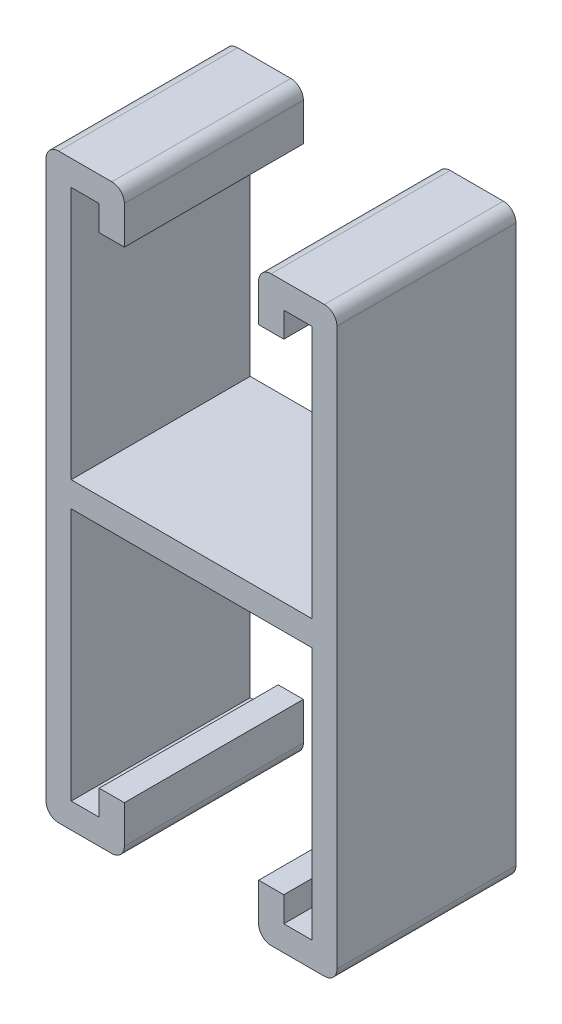
SolidWorks part; units mm, degrees
ref_plane "Plane1" through (0, 0, 0) normal (0, 0, 1) x (1, 0, 0)
ref_plane "Plane2" through (0, 0, 0) normal (0, 1, 0) x (1, 0, 0)
ref_plane "Plane3" through (0, 0, 0) normal (1, 0, 0) x (0, 0, -1)
sketch "Sketch1" plane through (0, 0, 0) normal (0, 0, 1) x (1, 0, 0)
  line L0 (-11.3109, 41.275) -> (-18.8516, 41.275)
  line L1 (-20.6375, 39.4891) -> (-20.6375, -39.4891)
  line L2 (25.727, 0) -> (-25.0678, 0) construction
  line L3 (20.6375, -39.4891) -> (20.6375, 39.4891)
  line L4 (18.8516, 41.275) -> (11.3109, 41.275)
  line L5 (9.525, 39.4891) -> (9.525, 34.1313)
  line L6 (-9.525, 39.4891) -> (-9.525, 34.1313)
  line L7 (-13.0969, 37.7031) -> (-13.0969, 34.1313)
  line L8 (-13.0969, 37.7031) -> (-17.0656, 37.7031)
  line L9 (-17.0656, 37.7031) -> (-17.0656, 1.7859)
  line L10 (-17.0656, 1.7859) -> (17.0656, 1.7859)
  line L11 (17.0656, 1.7859) -> (17.0656, 37.7031)
  line L12 (17.0656, 37.7031) -> (13.0969, 37.7031)
  line L13 (13.0969, 37.7031) -> (13.0969, 34.1313)
  line L14 (-13.0969, 34.1313) -> (-9.525, 34.1313)
  line L15 (9.525, 34.1313) -> (13.0969, 34.1313)
  line L16 (-11.3109, -41.275) -> (-18.8516, -41.275)
  line L17 (-13.0969, -37.7031) -> (-17.0656, -37.7031)
  line L18 (-13.0969, -37.7031) -> (-13.0969, -34.1313)
  line L19 (-9.525, -39.4891) -> (-9.525, -34.1313)
  line L20 (-13.0969, -34.1313) -> (-9.525, -34.1313)
  line L21 (18.8516, -41.275) -> (11.3109, -41.275)
  line L22 (9.525, -39.4891) -> (9.525, -34.1313)
  line L23 (9.525, -34.1313) -> (13.0969, -34.1313)
  line L24 (13.0969, -37.7031) -> (13.0969, -34.1313)
  line L25 (17.0656, -37.7031) -> (13.0969, -37.7031)
  line L26 (17.0656, -1.7859) -> (17.0656, -37.7031)
  line L27 (-17.0656, -37.7031) -> (-17.0656, -1.7859)
  line L28 (-17.0656, -1.7859) -> (17.0656, -1.7859)
  arc A0 (-11.3109, 41.275) -> (-9.525, 39.4891) centre (-11.3109, 39.4891) cw
  arc A1 (-20.6375, 39.4891) -> (-18.8516, 41.275) centre (-18.8516, 39.4891) cw
  arc A2 (-11.3109, -41.275) -> (-9.525, -39.4891) centre (-11.3109, -39.4891) ccw
  arc A3 (-20.6375, -39.4891) -> (-18.8516, -41.275) centre (-18.8516, -39.4891) ccw
  arc A4 (18.8516, 41.275) -> (20.6375, 39.4891) centre (18.8516, 39.4891) cw
  arc A5 (9.525, 39.4891) -> (11.3109, 41.275) centre (11.3109, 39.4891) cw
  arc A6 (18.8516, -41.275) -> (20.6375, -39.4891) centre (18.8516, -39.4891) ccw
  arc A7 (9.525, -39.4891) -> (11.3109, -41.275) centre (11.3109, -39.4891) ccw
  dimension "D2" = 1.7859
  dimension "D3" = 20.6375
  dimension "Width" = 41.275
  dimension "edge" = 11.1125
  dimension "D8" = 19.05
  dimension "ToeHt" = 7.1437
  dimension "D1" = 3.5719
  dimension "D4" = 41.275
  dimension "Height" = 82.55
  dimension "gauge" = 3.5719
extrude "Base-Extrude" add sketch "Sketch1" along normal mid plane 25.4
equation "\"D3@Sketch1\" = \"Width@Sketch1\" / 2"
equation "\"D2@Sketch1\" = \"gauge@Sketch1\" / 2"
equation "\"D8@Sketch1\" = \"Width@Sketch1\" - 2 * \"edge@Sketch1\""
equation "\"gauge@Sketch1\" = \"ToeHt@Sketch1\" / 2"
equation "\"D4@Sketch1\" = \"Height@Sketch1\" / 2"
